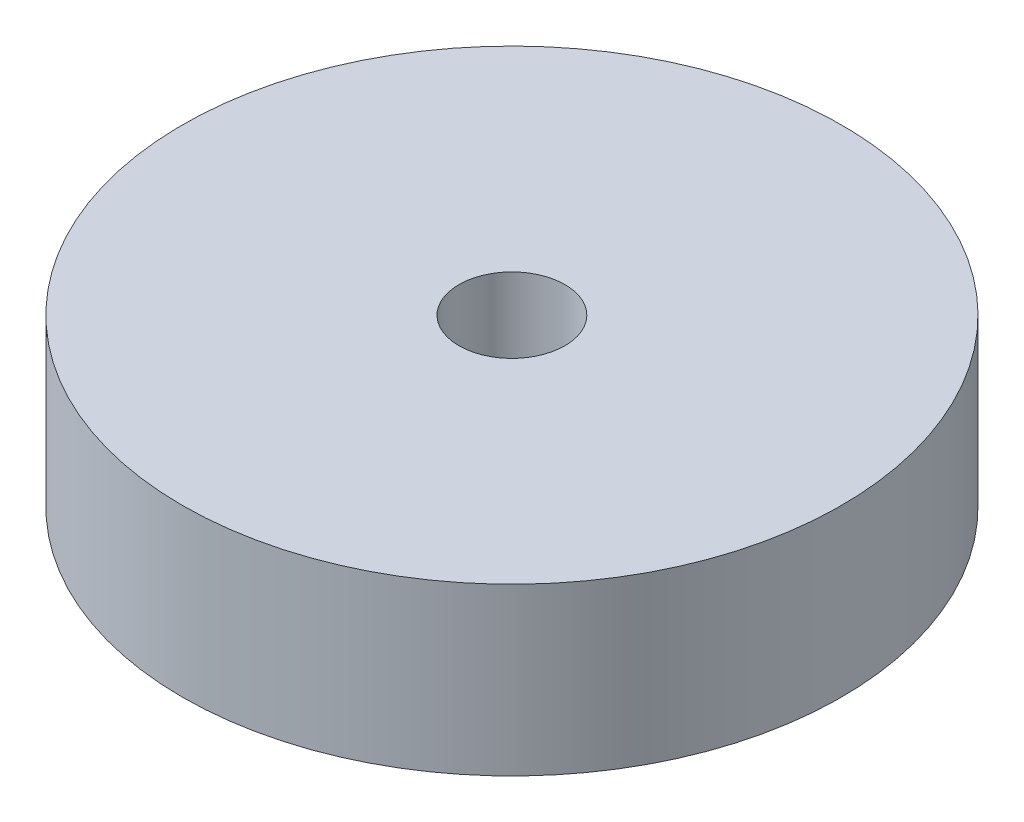
SolidWorks part; units mm, degrees
ref_plane "Front Plane" through (0, 0, 0) normal (0, 0, 1) x (1, 0, 0)
ref_plane "Top Plane" through (0, 0, 0) normal (0, 1, 0) x (1, 0, 0)
ref_plane "Right Plane" through (0, 0, 0) normal (1, 0, 0) x (0, 0, -1)
sketch "Sketch1" plane through (0, 0, 0) normal (0, 1, 0) x (1, 0, 0)
  circle A0 centre (0, 0) radius 15.875
  dimension "D1" = 31.75
extrude "Boss-Extrude1" add sketch "Sketch1" along normal blind 8
hole_wizard "1/4-20 Tapped Hole1" positions "Sketch2" profile "Sketch3" tap size "1/4-20" standard "ANSI Inch" end condition through all
sketch "Sketch2" plane through (0, 8, 0) normal (0, 1, 0) x (1, 0, 0)
  point P0 (0, 0)
sketch "Sketch3" plane through (0, 8, 0) normal (1, 0, 0) x (0, 0, 1)
  line L0 (0, 0) -> (0, 8)
  line L1 (0, 8) -> (2.5527, 8)
  line L2 (2.5527, 8) -> (2.5527, 0)
  line L5 (2.5527, 0) -> (0, 0)
  line L11 (0, -6.35) -> (0, 107.95) construction
  dimension "Thru Tap Drill Dia." = 5.1054
  dimension "Thru Tap Drill Depth" = 8
cosmetic thread "Hole Thread1" parameters "D2"=6.35
